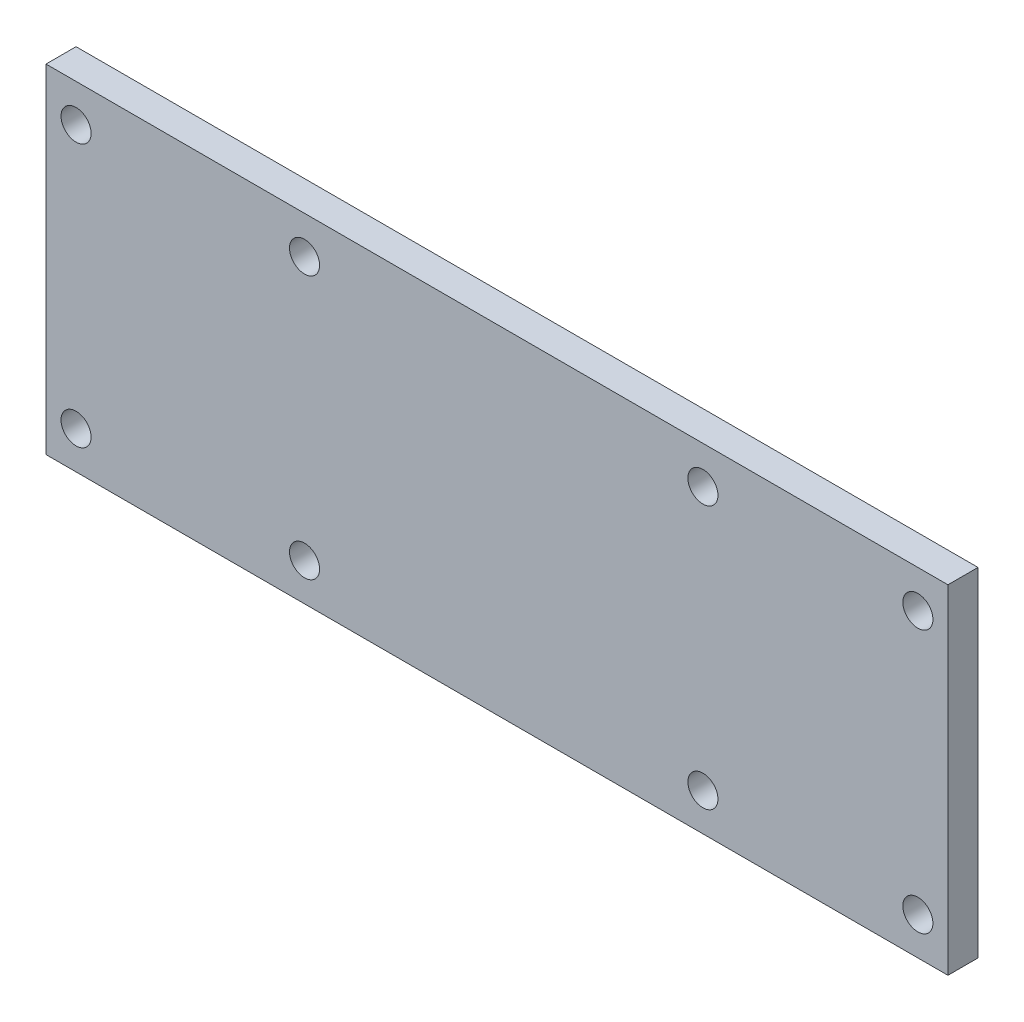
SolidWorks part; units mm, degrees
ref_plane "Front Plane" through (0, 0, 0) normal (0, 0, 1) x (1, 0, 0)
ref_plane "Top Plane" through (0, 0, 0) normal (0, 1, 0) x (1, 0, 0)
ref_plane "Right Plane" through (0, 0, 0) normal (1, 0, 0) x (0, 0, -1)
sketch "Esquisse1" plane through (0, 0, 0) normal (0, 0, 1) x (1, 0, 0)
  line L1 (-60, 22.5) -> (60, 22.5)
  line L2 (-60, 22.5) -> (-60, -22.5)
  line L3 (-60, -22.5) -> (60, -22.5)
  line L4 (60, 22.5) -> (60, -22.5)
  line L5 (-60, 22.5) -> (60, -22.5) construction
  line L6 (-60, -22.5) -> (60, 22.5) construction
  circle A0 centre (56, -17.5) radius 2
  circle A1 centre (27.4, -17.5) radius 2
  circle A2 centre (-25.6, -17.5) radius 2
  circle A3 centre (-56, -17.5) radius 2
  circle A4 centre (-25.6, 17.5) radius 2
  circle A5 centre (27.4, 17.5) radius 2
  circle A6 centre (56, 17.5) radius 2
  circle A7 centre (-56, 17.5) radius 2
  circle A8 centre (-56, -17.5) radius 2 construction
  circle A9 centre (-25.6, -17.5) radius 2 construction
  circle A11 centre (27.4, -17.5) radius 2 construction
  circle A12 centre (-25.6, 17.5) radius 2 construction
  circle A13 centre (-56, 17.5) radius 2 construction
  circle A14 centre (27.4, -17.5) radius 2 construction
  circle A15 centre (-56, -17.5) radius 2 construction
  circle A17 centre (27.4, 17.5) radius 2 construction
  circle A18 centre (27.4, 17.5) radius 2 construction
  circle A19 centre (56, -17.5) radius 2 construction
  circle A20 centre (56, 17.5) radius 2 construction
  point P0 (0, 0)
  point P36 (20.65, 18.2385)
  point P37 (53.7402, 24.5)
  point P40 (55.3203, 18.2385)
  dimension "D1" = 45
  dimension "D2" = 120
extrude "Boss.-Extru.1" add sketch "Esquisse1" along normal blind 4
